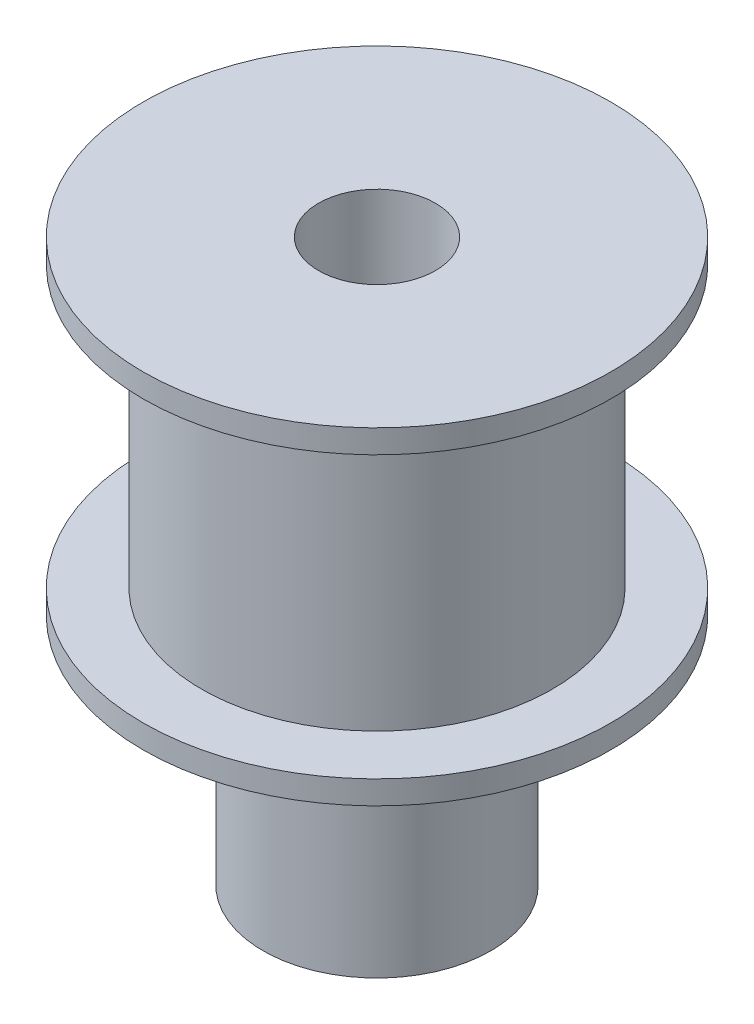
SolidWorks part; units mm, degrees
ref_plane "Front Plane" through (0, 0, 0) normal (0, 0, 1) x (1, 0, 0)
ref_plane "Top Plane" through (0, 0, 0) normal (0, 1, 0) x (1, 0, 0)
ref_plane "Right Plane" through (0, 0, 0) normal (1, 0, 0) x (0, 0, -1)
sketch "Sketch1" plane through (0, 0, 0) normal (0, 0, 1) x (1, 0, 0)
  line L0 (-2.5, 0) -> (-2.5, 24)
  line L1 (-2.5, 24) -> (-10, 24)
  line L2 (-10, 24) -> (-10, 23)
  line L3 (-10, 23) -> (-7.5, 23)
  line L4 (-7.5, 23) -> (-7.5, 11)
  line L5 (-7.5, 11) -> (-10, 11)
  line L6 (-10, 11) -> (-10, 10)
  line L7 (-10, 10) -> (-4.875, 10)
  line L8 (-4.875, 10) -> (-4.875, 0)
  line L9 (-4.875, 0) -> (-2.5, 0)
  line L10 (0, 0) -> (0, 23.1903) construction
  line L11 (0, 0) -> (-4.875, 0) construction
  dimension "D1" = 24
  dimension "D2" = 5
  dimension "D3" = 15
  dimension "D4" = 9.75
  dimension "D5" = 20
  dimension "D6" = 1
  dimension "D7" = 1
  dimension "D8" = 14
revolve "Revolve1" add sketch "Sketch1" angle 360 about L10
